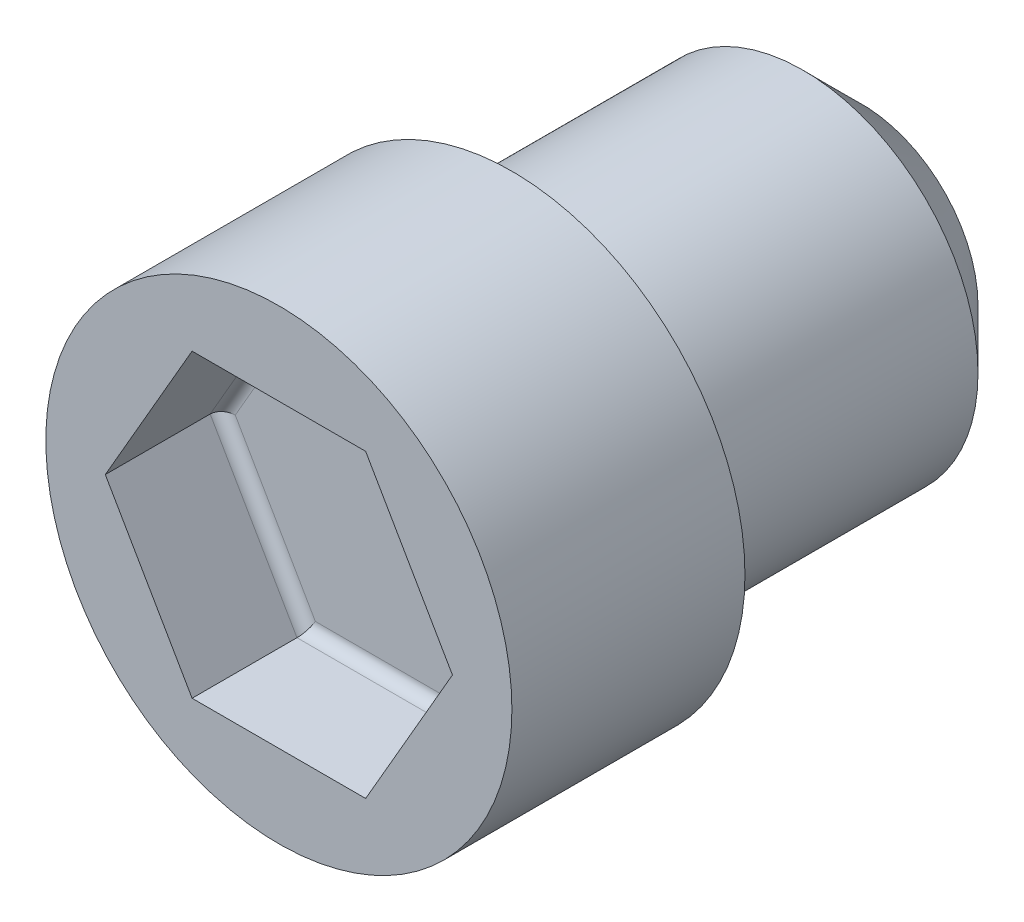
SolidWorks part; units mm, degrees
ref_plane "Front Plane" through (0, 0, 0) normal (1, 0, 0) x (0, 1, 0)
ref_plane "Top Plane" through (0, 0, 0) normal (0, 0, 1) x (0, 1, 0)
ref_plane "Right Plane" through (0, 0, 0) normal (0, 1, 0) x (-1, 0, 0)
sketch "Sketch3" plane through (0, 0, 0) normal (0, 0, 1) x (0, 1, 0)
  circle A0 centre (0, 0) radius 1.5
  dimension "D1" = 3
extrude "Boss-Extrude1" add sketch "Sketch3" along normal blind 3
sketch "Sketch4" plane through (0, 0, 3) normal (0, 0, 1) x (1, 0, 0)
  circle A0 centre (0, 0) radius 2
  dimension "D1" = 4
extrude "Boss-Extrude2" add sketch "Sketch4" along normal blind 2 contours A0
sketch "Sketch5" plane through (0, 0, 5) normal (0, 0, 1) x (1, 0, 0)
  line L0 (0, 2) -> (0, -2) construction
  line L2 (1.4896, 0) -> (0.7448, 1.29)
  line L3 (0.7448, 1.29) -> (-0.7448, 1.29)
  line L4 (-0.7448, 1.29) -> (-1.4896, 0)
  line L5 (-1.4896, 0) -> (-0.7448, -1.29)
  line L6 (-0.7448, -1.29) -> (0.7448, -1.29)
  line L7 (0.7448, -1.29) -> (1.4896, 0)
  circle A0 centre (0, 0) radius 2 construction
  circle A1 centre (0, 0) radius 1.29 construction
  dimension "D1" = 2.58
extrude "Cut-Extrude1" cut sketch "Sketch5" against normal blind 1
chamfer "Chamfer3" distance 0.5 angle 45 1 edges at (1.5, 0, 0)
fillet "Fillet1" radius 0.1 6 edges at (0, -1.29, 4) (1.1172, -0.645, 4) (1.1172, 0.645, 4) (0, 1.29, 4) (-1.1172, -0.645, 4) (-1.1172, 0.645, 4)
